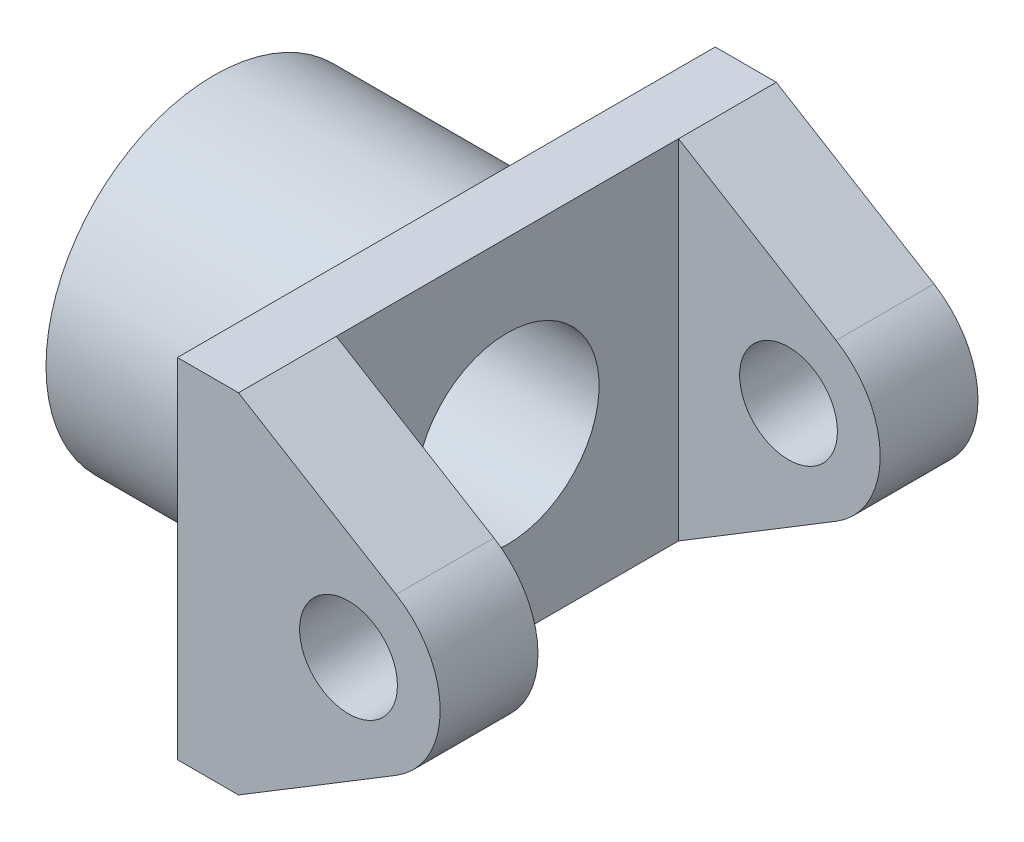
SolidWorks part; units mm, degrees
ref_plane "Front Plane" through (0, 0, 0) normal (0, 0, 1) x (1, 0, 0)
ref_plane "Top Plane" through (0, 0, 0) normal (0, 1, 0) x (1, 0, 0)
ref_plane "Right Plane" through (0, 0, 0) normal (1, 0, 0) x (0, 0, -1)
sketch "Sketch1" plane through (0, 0, 0) normal (0, 0, 1) x (1, 0, 0)
  line L0 (-28, 28.5) -> (-28, -28.5)
  line L2 (-28, 28.5) -> (-18, 28.5)
  line L3 (-28, -28.5) -> (-18, -28.5)
  line L4 (-18, -28.5) -> (7.7931, -12.8167)
  line L5 (-18, 28.5) -> (7.7931, 12.8167)
  circle A0 centre (0, 0) radius 8
  arc A1 (7.7931, -12.8167) -> (7.7931, 12.8167) centre (0, 0) ccw
  point P3 (0, 0)
  point P6 (-28, 0)
  dimension "D1" = 16
  dimension "D2" = 30
  dimension "D3" = 57
  dimension "D4" = 28
  dimension "D5" = 10
extrude "Boss-Extrude1" add sketch "Sketch1" against normal blind 16
sketch "Sketch2" plane through (-28, 0, 0) normal (-1, 0, 0) x (0, 0, 1)
  line L1 (-16, 28.5) -> (72, 28.5)
  line L2 (-16, 28.5) -> (-16, -28.5)
  line L3 (-16, -28.5) -> (72, -28.5)
  line L4 (72, 28.5) -> (72, -28.5)
  point P5 (-16, -28.5)
  dimension "D1" = 88
extrude "Boss-Extrude2" add sketch "Sketch2" against normal blind 10
sketch "Sketch3" plane through (0, 0, 72) normal (0, 0, 1) x (1, 0, 0)
  line L3 (7.7931, 12.8167) -> (-18, 28.5)
  line L12 (-18, 28.5) -> (-18, -28.5)
  line L13 (-18, -28.5) -> (7.7931, -12.8167)
  line L14 (7.7931, 12.8167) -> (-18, 28.5)
  line L15 (-18, 28.5) -> (-18, -28.5)
  line L16 (-18, -28.5) -> (7.7931, -12.8167)
  circle A0 centre (0, 0) radius 8 construction
  arc A1 (7.7931, -12.8167) -> (7.7931, 12.8167) centre (0, 0) ccw
  arc A2 (7.7931, -12.8167) -> (7.7931, 12.8167) centre (0, 0) ccw
  circle A3 centre (0, 0) radius 8
  dimension "D2" = 0
extrude "Boss-Extrude3" add sketch "Sketch3" against normal blind 16
sketch "Sketch4" plane through (-28, 0, 0) normal (-1, 0, 0) x (0, 0, 1)
  line L0 (-16, 28.5) -> (72, 28.5) construction
  line L1 (47, 4) -> (47, -4)
  line L2 (47, 4) -> (42.4568, 4)
  line L3 (47, -4) -> (42.4568, -4)
  circle A0 centre (28, 0) radius 27.5
  arc A1 (42.4568, 4) -> (42.4568, -4) centre (28, 0) ccw
  point P2 (47, 0)
  point P8 (28, 28.5)
  dimension "D1" = 55
  dimension "D2" = 30
  dimension "D3" = 19
  dimension "D4" = 8
extrude "Boss-Extrude4" add sketch "Sketch4" along normal blind 38
sketch "Sketch5" plane through (-18, 0, 0) normal (1, 0, 0) x (0, 0, -1)
  line L3 (-47, -4) -> (-47, 4) construction
  line L4 (-47, 4) -> (-42.4568, 4) construction
  line L5 (-42.4568, -4) -> (-47, -4) construction
  line L6 (-47, -4) -> (-47, 4)
  line L7 (-47, 4) -> (-42.4568, 4)
  line L8 (-42.4568, -4) -> (-47, -4)
  arc A1 (-42.4568, -4) -> (-42.4568, 4) centre (-28, 0) ccw construction
  arc A2 (-42.4568, -4) -> (-42.4568, 4) centre (-28, 0) ccw
extrude "Cut-Extrude2" cut sketch "Sketch5" against normal through all
